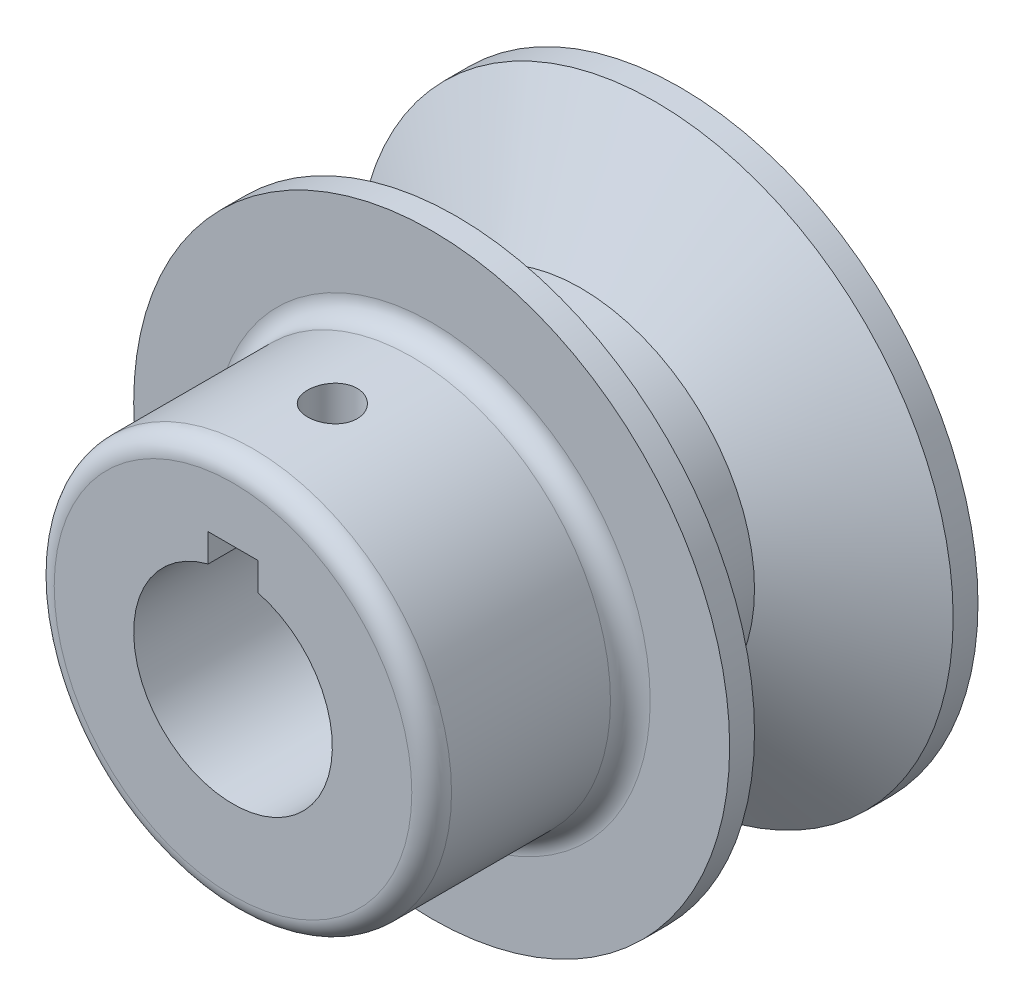
SolidWorks part; units mm, degrees
material "6061 Alloy"
ref_plane "Front Plane" through (0, 0, 0) normal (0, 0, 1) x (1, 0, 0)
ref_plane "Top Plane" through (0, 0, 0) normal (0, 1, 0) x (1, 0, 0)
ref_plane "Right Plane" through (0, 0, 0) normal (1, 0, 0) x (0, 0, -1)
sketch "Sketch3" plane through (0, 0, 0) normal (1, 0, 0) x (0, 0, -1)
  line L0 (0, 6.35) -> (28.575, 6.35)
  line L1 (28.575, 6.35) -> (28.575, 19.05)
  line L2 (28.575, 19.05) -> (26.9875, 19.05)
  line L3 (22.225, 11.1125) -> (19.05, 11.1125)
  line L4 (12.7, 19.05) -> (14.2875, 19.05)
  line L5 (12.7, 19.05) -> (12.7, 12.7)
  line L6 (12.7, 12.7) -> (0, 12.7)
  line L7 (0, 12.7) -> (0, 6.35)
  line L8 (14.2875, 19.05) -> (19.05, 11.1125)
  line L9 (26.9875, 19.05) -> (22.225, 11.1125)
  line L10 (0, 0) -> (115.3497, 0) construction
  dimension "D1" = 28.575
  dimension "D2" = 15.875
  dimension "D3" = 7.9375
  dimension "D4" = 3.175
  dimension "D5" = 4.7625
  dimension "D6" = 12.7
  dimension "D7" = 19.05
  dimension "D8" = 6.35
  dimension "D9" = 12.7
revolve "Revolve2" add sketch "Sketch3" angle 360 about L10
sketch "Sketch4" plane through (0, 0, 0) normal (0, 0, 1) x (1, 0, 0)
  line L1 (1.5875, 4.7625) -> (-1.5875, 4.7625)
  line L2 (1.5875, 4.7625) -> (1.5875, 7.9375)
  line L3 (1.5875, 7.9375) -> (-1.5875, 7.9375)
  line L4 (-1.5875, 4.7625) -> (-1.5875, 7.9375)
  dimension "D1" = 3.175
  dimension "D2" = 3.175
  dimension "D3" = 4.7625
  dimension "D4" = 1.5875
extrude "Cut-Extrude2" cut sketch "Sketch4" against normal through all
sketch "Sketch5" plane through (0, 0, 0) normal (0, 1, 0) x (1, 0, 0)
  line L0 (-12.7, 0) -> (12.7, 0) construction
  line L1 (-12.7, 12.7) -> (-12.7, 0) construction
  circle A0 centre (0, 6.35) radius 1.5875
  dimension "D3" = 3.175
  dimension "D1" = 6.35
  dimension "D2" = 12.7
extrude "Cut-Extrude3" cut sketch "Sketch5" along normal through all
fillet "Fillet1" radius 1.27 2 edges at (12.7, 0, -12.7) (12.7, 0, 0)
